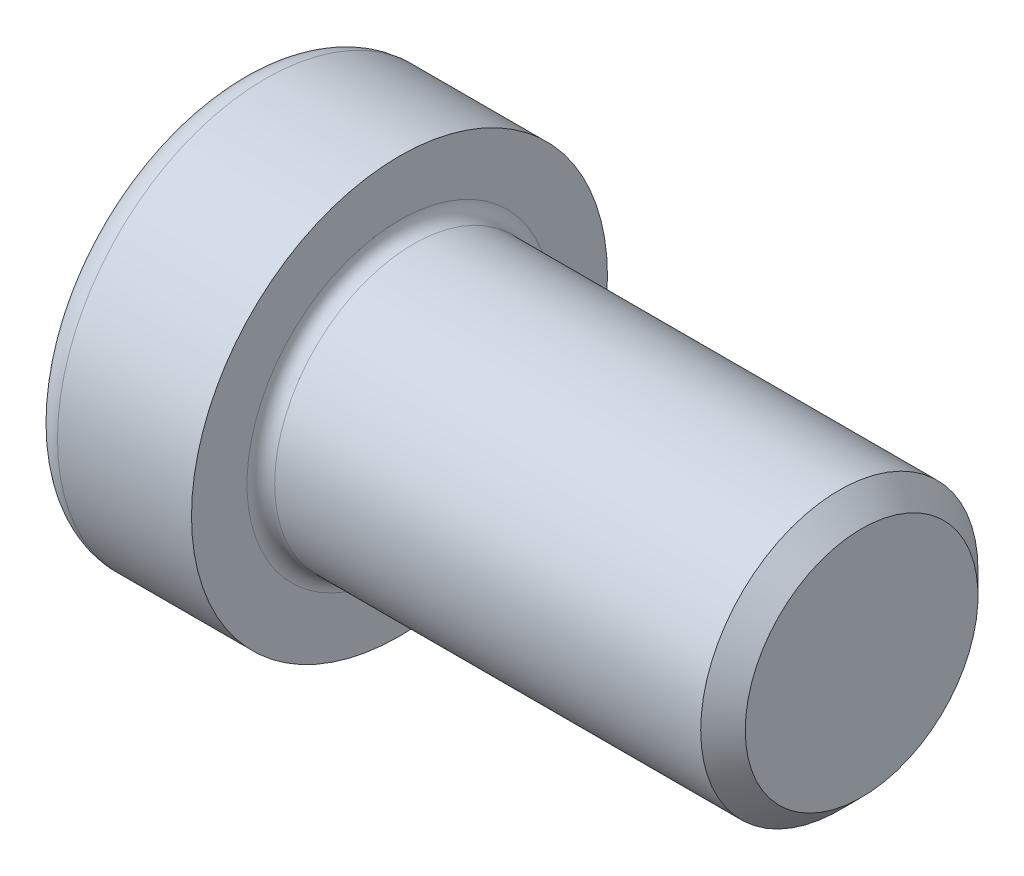
SolidWorks part; units mm, degrees
revolve "Base-Revolve" add sketch "BodySke"
sketch "BodySke" plane through (0, 0, 0) normal (0, 0, 1) x (1, 0, 0)
  line L0 (0, 0) -> (0, 9)
  line L1 (0, 9) -> (7, 9)
  line L2 (7, 9) -> (7, 6)
  line L3 (7, 6) -> (26.036, 6)
  line L4 (27, 5.036) -> (27, 0)
  line L5 (27, 0) -> (0, 0)
  line L6 (-31.75, 0) -> (127, 0) construction
  line L8 (27, 5.036) -> (26.036, 6)
  line L10 (27, -5.036) -> (26.036, -6) construction
  line L11 (8.75, 4.525) -> (8.75, -1.825) construction
  line L12 (12.25, 4.525) -> (12.25, -1.825) construction
  line L13 (-33, 4.525) -> (-33, -1.825) construction
  dimension "Head_ht" = 7
  dimension "Length" = 20
  dimension "Body_ch_ang" = 45
  dimension "Diameter" = 12
  dimension "Minor_dia" = 10.072
  dimension "Advance" = 1.75
  dimension "Thread_nom" = 14.75
  dimension "Thread_length" = 60
  dimension "Head_dia" = 18
cosmetic thread "ThreadCosmetic"
fillet "Fillet1" radius 0.6 1 edges at (7, 0, 6)
fillet "Fillet2" radius 1.2 1 edges at (0, 0, 9)
material "AISI 316 Нержавеющая сталь, лист (SS)"
ref_plane "Plane1" through (0, 0, 0) normal (0, 0, 1) x (1, 0, 0)
ref_plane "Plane2" through (0, 0, 0) normal (0, 1, 0) x (1, 0, 0)
ref_plane "Plane3" through (0, 0, 0) normal (1, 0, 0) x (0, 0, -1)
other "Configuration Table"
sketch "Sketch2" plane through (0, 0, 0) normal (0, 0, 1) x (1, 0, 0)
  line L0 (0, 4) -> (5, 4)
  line L1 (5, 4) -> (7.3094, 0)
  line L2 (-31.75, 0) -> (127, 0) construction
  line L3 (7.3094, 0) -> (0, 0)
  line L4 (0, 0) -> (0, 4)
  line L6 (0, 0) -> (47.625, 0) construction
  dimension "D1" = 4
  dimension "D2" = 60
  dimension "Depth" = 5
revolve "Hex-PreBroach" cut sketch "Sketch2" angle 360 about L6
sketch "Sketch3" plane through (0, 0, 0) normal (-1, 0, 0) x (0, 0.5, 0.866)
  line L0 (2.3094, 4) -> (-2.3094, 4)
  line L1 (-2.3094, 4) -> (-4.6188, 0)
  line L2 (2.3094, 4) -> (4.6188, 0)
  line L3 (2.3094, -4) -> (4.6188, 0)
  line L4 (2.3094, -4) -> (-2.3094, -4)
  line L5 (-2.3094, -4) -> (-4.6188, 0)
  dimension "D1" = 4
  dimension "D2" = 4
  dimension "Hex_size" = 8
extrude "Hex" cut sketch "Sketch3" against normal blind 5
sketch "ThdSchSke" plane through (0, 0, 0) normal (0, 0, 1) x (1, 0, 0)
  line L0 (12.25, -5.036) -> (11.575, -6)
  line L1 (12.25, -5.036) -> (12.925, -6)
  line L2 (12.925, -6) -> (12.925, -7.5)
  line L3 (-3.175, 0) -> (5.1513, 0) construction
  line L4 (0, 7.8) -> (0, -7.8) construction
  line L5 (12.925, -7.5) -> (11.575, -7.5)
  line L6 (11.575, -7.5) -> (11.575, -6)
  dimension "Thread_minor" = 10.072
  dimension "Diameter" = 12
  dimension "Start" = 12.25
revolve "ThreadSchematic" [suppressed] cut sketch "ThdSchSke" angle 360 about L3
pattern_linear "ThdSchPat" [suppressed]
equation "\"D2@Sketch3\" = \"Hex_size@Sketch3\" / 2"
equation "\"D1@Sketch3\" = \"Hex_size@Sketch3\" / 2"
equation "\"D1@Sketch2\" = \"Hex_size@Sketch3\" / 2"
equation "\"Thread_minor@ThreadCosmetic\"  =  \"Minor_dia@BodySke\""
equation "\"Depth@Sketch2\" =  \"Key_eng@Hex\""
equation "\"Thread_length@ThreadCosmetic\" = ((sgn( (\"Length@BodySke\" - \"Advance@BodySke\" * 3.0) - \"Thread_nom@BodySke\" )-1)*( (\"Length@BodySke\" - \"Advance@BodySke\" * 3.0) - \"Thread_nom@BodySke\" ))/-2+ \"Thread_nom@BodySke\""
equation "\"Thread_minor@ThdSchSke\" = \"Minor_dia@BodySke\""
equation "\"Diameter@ThdSchSke\" = \"Diameter@BodySke\""
equation "\"Overcut@ThdSchSke\" = \"Diameter@BodySke\" * 1.25"
equation "\"Start@ThdSchSke\" = \"Head_ht@BodySke\" + \"Length@BodySke\" - \"Thread_length@ThreadCosmetic\"  '---Non-countersunk---"
equation "\"Num_threads@ThdSchPat\" = int( \"Thread_length@ThreadCosmetic\" / \"Advance@BodySke\" + 0.999 )  + 1"
equation "\"Advance@ThdSchPat\" = \"Thread_length@ThreadCosmetic\" /  (\"Num_threads@ThdSchPat\" - 1) 'relax it"
equation "\"Num_threads@ThdSchPat\" = \"Num_threads@ThdSchPat\" - sgn( \"Num_threads@ThdSchPat\" - 1) '---chamfered tips only---"
